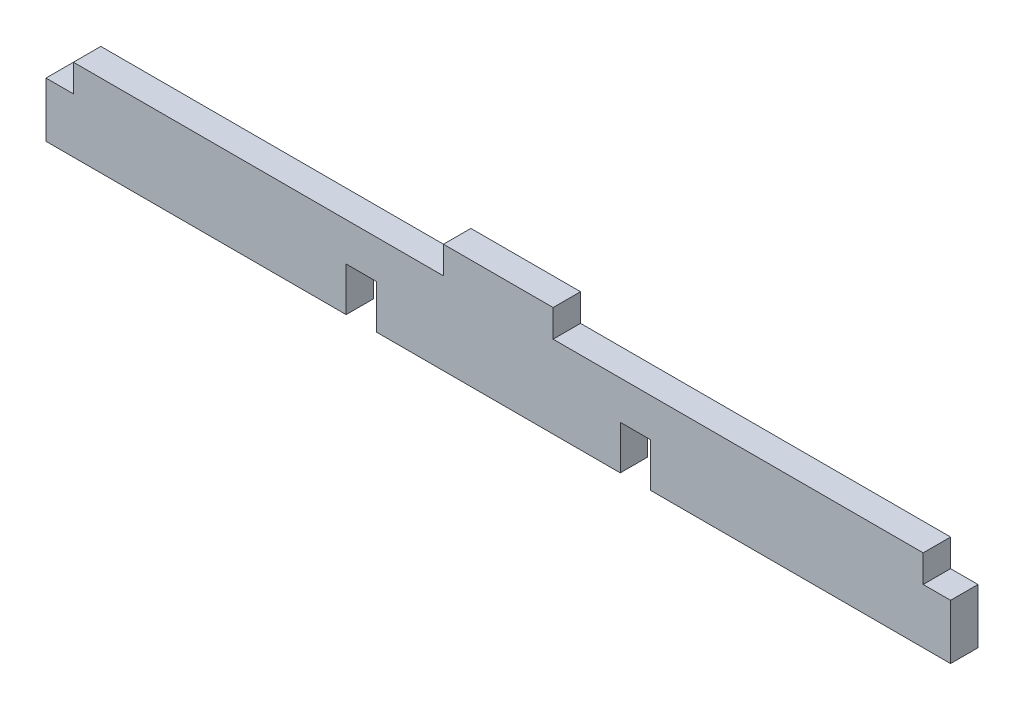
SolidWorks part; units mm, degrees
ref_plane "Front Plane" through (0, 0, 0) normal (0, 0, 1) x (1, 0, 0)
ref_plane "Top Plane" through (0, 0, 0) normal (0, 1, 0) x (1, 0, 0)
ref_plane "Right Plane" through (0, 0, 0) normal (1, 0, 0) x (0, 0, -1)
sketch "Model" plane through (0, 0, 0) normal (0, 0, 1) x (1, 0, 0)
  line L0 (388.2957, -195.6456) -> (388.2957, -203.6456)
  line L1 (393.7957, -195.6456) -> (388.2957, -195.6456)
  line L2 (493.5457, -188.6456) -> (426.0457, -188.6456)
  line L3 (393.7957, -203.6456) -> (393.7957, -195.6456)
  line L4 (393.7957, -203.6456) -> (438.2957, -203.6456)
  line L5 (426.0457, -188.6456) -> (426.0457, -183.6456)
  line L6 (426.0457, -183.6456) -> (406.0457, -183.6456)
  line L7 (493.5457, -193.6456) -> (493.5457, -188.6456)
  line L8 (406.0457, -188.6456) -> (338.5457, -188.6456)
  line L9 (333.5457, -193.6456) -> (333.5457, -203.6456)
  line L10 (443.7957, -195.6456) -> (438.2957, -195.6456)
  line L11 (443.7957, -203.6456) -> (443.7957, -195.6456)
  line L12 (438.2957, -195.6456) -> (438.2957, -203.6456)
  line L13 (338.5457, -188.6456) -> (338.5457, -193.6456)
  line L14 (406.0457, -183.6456) -> (406.0457, -188.6456)
  line L15 (443.7957, -203.6456) -> (498.5457, -203.6456)
  line L16 (498.5457, -203.6456) -> (498.5457, -193.6456)
  line L17 (498.5457, -193.6456) -> (493.5457, -193.6456)
  line L18 (338.5457, -193.6456) -> (333.5457, -193.6456)
  line L19 (333.5457, -203.6456) -> (388.2957, -203.6456)
  line L20 (422.6665, -199.5351) -> (427.6665, -199.5351)
  line L21 (425.6665, -200.5351) -> (427.6665, -199.5351)
  line L22 (425.6665, -198.5351) -> (427.6665, -199.5351)
  line L23 (420.1665, -197.3376) -> (420.1665, -199.5355)
  line L24 (420.1665, -199.5355) -> (419.1487, -199.5355)
  line L25 (419.1487, -199.5355) -> (418.5915, -199.4668)
  line L26 (418.5915, -199.4668) -> (418.2559, -199.3606)
  line L27 (418.2559, -199.3606) -> (418.0826, -199.2264)
  line L28 (418.0826, -199.2264) -> (418.0248, -199.0734)
  line L29 (418.0248, -199.0734) -> (418.0248, -197.8184)
  line L30 (418.0248, -197.8184) -> (418.0455, -197.7197)
  line L31 (418.0455, -197.7197) -> (418.1076, -197.6295)
  line L32 (418.1076, -197.6295) -> (418.3558, -197.475)
  line L33 (418.3558, -197.475) -> (418.7164, -197.372)
  line L34 (418.7164, -197.372) -> (419.1487, -197.3376)
  line L35 (419.1487, -197.3376) -> (420.1665, -197.3376)
  line L36 (420.1665, -201.6456) -> (420.1665, -197.3376)
  line L37 (420.1665, -197.3376) -> (419.1487, -197.3376)
  line L38 (419.1487, -197.3376) -> (418.7164, -197.372)
  line L39 (418.7164, -197.372) -> (418.3558, -197.475)
  line L40 (418.3558, -197.475) -> (418.1076, -197.6295)
  line L41 (418.1076, -197.6295) -> (418.0455, -197.7197)
  line L42 (418.0455, -197.7197) -> (418.0248, -197.8184)
  line L43 (418.0248, -197.8184) -> (418.0248, -199.0733)
  line L44 (418.0248, -199.0733) -> (418.0826, -199.2262)
  line L45 (418.0826, -199.2262) -> (418.2559, -199.3604)
  line L46 (418.2559, -199.3604) -> (418.5915, -199.4666)
  line L47 (418.5915, -199.4666) -> (419.1487, -199.5353)
  line L48 (419.1487, -199.5353) -> (418.5977, -199.5993)
  line L49 (418.5977, -199.5993) -> (418.2559, -199.7039)
  line L50 (418.2559, -199.7039) -> (418.0826, -199.8428)
  line L51 (418.0826, -199.8428) -> (418.0248, -199.9973)
  line L52 (418.0248, -199.9973) -> (418.0248, -201.1648)
  line L53 (418.0248, -201.1648) -> (418.0455, -201.2585)
  line L54 (418.0455, -201.2585) -> (418.1076, -201.3459)
  line L55 (418.1076, -201.3459) -> (418.3558, -201.502)
  line L56 (418.3558, -201.502) -> (418.7195, -201.6097)
  line L57 (418.7195, -201.6097) -> (419.1487, -201.6456)
  line L58 (419.1487, -201.6456) -> (420.1665, -201.6456)
  line L59 (419.1487, -199.5351) -> (420.1665, -199.5351)
  line L60 (420.1665, -199.5351) -> (420.1665, -201.6456)
  line L61 (420.1665, -201.6456) -> (419.1487, -201.6456)
  line L62 (419.1487, -201.6456) -> (418.7195, -201.6097)
  line L63 (418.7195, -201.6097) -> (418.3558, -201.5019)
  line L64 (418.3558, -201.5019) -> (418.1076, -201.3458)
  line L65 (418.1076, -201.3458) -> (418.0455, -201.2584)
  line L66 (418.0455, -201.2584) -> (418.0248, -201.1648)
  line L67 (418.0248, -201.1648) -> (418.0248, -199.9972)
  line L68 (418.0248, -199.9972) -> (418.0826, -199.8426)
  line L69 (418.0826, -199.8426) -> (418.2559, -199.7037)
  line L70 (418.2559, -199.7037) -> (418.5977, -199.5991)
  line L71 (418.5977, -199.5991) -> (419.1487, -199.5351)
  line L72 (417.1696, -197.3376) -> (417.1696, -201.6456)
  line L73 (417.1696, -201.6456) -> (415.0404, -201.6456)
  line L74 (415.0404, -201.6456) -> (417.1696, -201.6456)
  line L75 (417.1696, -201.6456) -> (417.1696, -199.5166)
  line L76 (417.1696, -199.5166) -> (415.3401, -199.5166)
  line L77 (415.3401, -199.5166) -> (417.1696, -199.5166)
  line L78 (417.1696, -199.5166) -> (417.1696, -197.3376)
  line L79 (413.0487, -197.3376) -> (413.4897, -197.3728)
  line L80 (413.4897, -197.3728) -> (413.8511, -197.4781)
  line L81 (413.8511, -197.4781) -> (414.0922, -197.6334)
  line L82 (414.0922, -197.6334) -> (414.1525, -197.7222)
  line L83 (414.1525, -197.7222) -> (414.1726, -197.8184)
  line L84 (414.1726, -197.8184) -> (414.1525, -197.7222)
  line L85 (414.1525, -197.7222) -> (414.0922, -197.6334)
  line L86 (414.0922, -197.6334) -> (413.8511, -197.4781)
  line L87 (413.8511, -197.4781) -> (413.4897, -197.3728)
  line L88 (412.6077, -197.3728) -> (412.2464, -197.4781)
  line L89 (412.2464, -197.4781) -> (412.0052, -197.6334)
  line L90 (412.0052, -197.6334) -> (411.9449, -197.7222)
  line L91 (411.9449, -197.7222) -> (411.9248, -197.8184)
  line L92 (411.9248, -197.8184) -> (411.9248, -199.529)
  line L93 (411.9248, -199.529) -> (411.9449, -199.6252)
  line L94 (411.9449, -199.6252) -> (412.0052, -199.714)
  line L95 (412.0052, -199.714) -> (412.2464, -199.8694)
  line L96 (412.2464, -199.8694) -> (412.6077, -199.9747)
  line L97 (412.6077, -199.9747) -> (413.0487, -200.0098)
  line L98 (413.0487, -200.0098) -> (413.7231, -199.9099)
  line L99 (413.7231, -199.9099) -> (413.9541, -199.7835)
  line L100 (413.9541, -199.7835) -> (414.1726, -199.529)
  line L101 (414.1726, -199.529) -> (414.1726, -201.6456)
  line L102 (414.1726, -201.6456) -> (411.9997, -201.6456)
  line L103 (411.9997, -201.6456) -> (414.1726, -201.6456)
  line L104 (414.1726, -201.6456) -> (414.1726, -199.529)
  line L105 (414.1726, -199.529) -> (413.9541, -199.7835)
  line L106 (413.9541, -199.7835) -> (413.7231, -199.9099)
  line L107 (413.7231, -199.9099) -> (413.0487, -200.0098)
  line L108 (413.0487, -200.0098) -> (412.6077, -199.9747)
  line L109 (412.6077, -199.9747) -> (412.2464, -199.8694)
  line L110 (412.2464, -199.8694) -> (412.0052, -199.714)
  line L111 (412.0052, -199.714) -> (411.9449, -199.6252)
  line L112 (411.9449, -199.6252) -> (411.9248, -199.529)
  line L113 (411.9248, -199.529) -> (411.9248, -197.8184)
  line L114 (411.9248, -197.8184) -> (411.9449, -197.7222)
  line L115 (411.9449, -197.7222) -> (412.0052, -197.6334)
  line L116 (412.0052, -197.6334) -> (412.2464, -197.4781)
  line L117 (412.2464, -197.4781) -> (412.6077, -197.3728)
  line L118 (412.6077, -197.3728) -> (413.0487, -197.3376)
  line L119 (409.4248, -199.5351) -> (404.4248, -199.5351)
  line L120 (406.4248, -198.5351) -> (404.4248, -199.5351)
  line L121 (406.4248, -200.5351) -> (404.4248, -199.5351)
  line L122 (491.5457, -202.8873) -> (489.3478, -202.8873)
  line L123 (489.3478, -202.8873) -> (489.3478, -201.8695)
  line L124 (489.3478, -201.8695) -> (489.4165, -201.3123)
  line L125 (489.4165, -201.3123) -> (489.5227, -200.9766)
  line L126 (489.5227, -200.9766) -> (489.6569, -200.8034)
  line L127 (489.6569, -200.8034) -> (489.8099, -200.7456)
  line L128 (489.8099, -200.7456) -> (491.0649, -200.7456)
  line L129 (491.0649, -200.7456) -> (491.1636, -200.7663)
  line L130 (491.1636, -200.7663) -> (491.2538, -200.8283)
  line L131 (491.2538, -200.8283) -> (491.4083, -201.0765)
  line L132 (491.4083, -201.0765) -> (491.5113, -201.4371)
  line L133 (491.5113, -201.4371) -> (491.5457, -201.8695)
  line L134 (491.5457, -201.8695) -> (491.5457, -202.8873)
  line L135 (487.2377, -202.8873) -> (491.5457, -202.8873)
  line L136 (491.5457, -202.8873) -> (491.5457, -201.8695)
  line L137 (491.5457, -201.8695) -> (491.5113, -201.4371)
  line L138 (491.5113, -201.4371) -> (491.4083, -201.0765)
  line L139 (491.4083, -201.0765) -> (491.2538, -200.8283)
  line L140 (491.2538, -200.8283) -> (491.1636, -200.7663)
  line L141 (491.1636, -200.7663) -> (491.0649, -200.7456)
  line L142 (491.0649, -200.7456) -> (489.81, -200.7456)
  line L143 (489.81, -200.7456) -> (489.6571, -200.8034)
  line L144 (489.6571, -200.8034) -> (489.5228, -200.9766)
  line L145 (489.5228, -200.9766) -> (489.4167, -201.3123)
  line L146 (489.4167, -201.3123) -> (489.348, -201.8695)
  line L147 (489.348, -201.8695) -> (489.284, -201.3185)
  line L148 (489.284, -201.3185) -> (489.1794, -200.9766)
  line L149 (489.1794, -200.9766) -> (489.0405, -200.8034)
  line L150 (489.0405, -200.8034) -> (488.886, -200.7456)
  line L151 (488.886, -200.7456) -> (487.7185, -200.7456)
  line L152 (487.7185, -200.7456) -> (487.6248, -200.7663)
  line L153 (487.6248, -200.7663) -> (487.5374, -200.8283)
  line L154 (487.5374, -200.8283) -> (487.3813, -201.0765)
  line L155 (487.3813, -201.0765) -> (487.2736, -201.4402)
  line L156 (487.2736, -201.4402) -> (487.2377, -201.8695)
  line L157 (487.2377, -201.8695) -> (487.2377, -202.8873)
  line L158 (489.3482, -201.8695) -> (489.3482, -202.8873)
  line L159 (489.3482, -202.8873) -> (487.2377, -202.8873)
  line L160 (487.2377, -202.8873) -> (487.2377, -201.8695)
  line L161 (487.2377, -201.8695) -> (487.2736, -201.4402)
  line L162 (487.2736, -201.4402) -> (487.3814, -201.0765)
  line L163 (487.3814, -201.0765) -> (487.5375, -200.8283)
  line L164 (487.5375, -200.8283) -> (487.6249, -200.7663)
  line L165 (487.6249, -200.7663) -> (487.7185, -200.7456)
  line L166 (487.7185, -200.7456) -> (488.8861, -200.7456)
  line L167 (488.8861, -200.7456) -> (489.0407, -200.8034)
  line L168 (489.0407, -200.8034) -> (489.1796, -200.9766)
  line L169 (489.1796, -200.9766) -> (489.2842, -201.3185)
  line L170 (489.2842, -201.3185) -> (489.3482, -201.8695)
  line L171 (491.0649, -197.6425) -> (491.1611, -197.6626)
  line L172 (491.1611, -197.6626) -> (491.2499, -197.7229)
  line L173 (491.2499, -197.7229) -> (491.4052, -197.9641)
  line L174 (491.4052, -197.9641) -> (491.5105, -198.3254)
  line L175 (491.5105, -198.3254) -> (491.5457, -198.7664)
  line L176 (491.5457, -198.7664) -> (491.5105, -199.2074)
  line L177 (491.5105, -199.2074) -> (491.4052, -199.5688)
  line L178 (491.4052, -199.5688) -> (491.2499, -199.8099)
  line L179 (491.2499, -199.8099) -> (491.1611, -199.8702)
  line L180 (491.1611, -199.8702) -> (491.0649, -199.8903)
  line L181 (491.0649, -199.8903) -> (487.7185, -199.8903)
  line L182 (487.7185, -199.8903) -> (487.6223, -199.8702)
  line L183 (487.6223, -199.8702) -> (487.5335, -199.8099)
  line L184 (487.5335, -199.8099) -> (487.3782, -199.5688)
  line L185 (487.3782, -199.5688) -> (487.2729, -199.2074)
  line L186 (487.2729, -199.2074) -> (487.2377, -198.7664)
  line L187 (487.2377, -198.7664) -> (487.2729, -198.3254)
  line L188 (487.2729, -198.3254) -> (487.3782, -197.9641)
  line L189 (487.3782, -197.9641) -> (487.5335, -197.7229)
  line L190 (487.5335, -197.7229) -> (487.6223, -197.6626)
  line L191 (487.6223, -197.6626) -> (487.7185, -197.6425)
  line L192 (487.7185, -197.6425) -> (488.0244, -197.6425)
  line L193 (488.0244, -197.6425) -> (487.7185, -197.6425)
  line L194 (487.7185, -197.6425) -> (487.6223, -197.6626)
  line L195 (487.6223, -197.6626) -> (487.5335, -197.7229)
  line L196 (487.5335, -197.7229) -> (487.3782, -197.9641)
  line L197 (487.3782, -197.9641) -> (487.2729, -198.3254)
  line L198 (487.2729, -198.3254) -> (487.2377, -198.7664)
  line L199 (487.2377, -198.7664) -> (487.2729, -199.2074)
  line L200 (487.2729, -199.2074) -> (487.3782, -199.5688)
  line L201 (487.3782, -199.5688) -> (487.5335, -199.8099)
  line L202 (487.5335, -199.8099) -> (487.6223, -199.8702)
  line L203 (487.6223, -199.8702) -> (487.7185, -199.8903)
  line L204 (487.7185, -199.8903) -> (491.0649, -199.8903)
  line L205 (491.0649, -199.8903) -> (491.1611, -199.8702)
  line L206 (491.1611, -199.8702) -> (491.2499, -199.8099)
  line L207 (491.2499, -199.8099) -> (491.4052, -199.5688)
  line L208 (491.4052, -199.5688) -> (491.5105, -199.2074)
  line L209 (491.5105, -199.2074) -> (491.5457, -198.7664)
  line L210 (491.5457, -198.7664) -> (491.5105, -198.3254)
  line L211 (491.5105, -198.3254) -> (491.4052, -197.9641)
  line L212 (491.4052, -197.9641) -> (491.2499, -197.7229)
  line L213 (491.2499, -197.7229) -> (491.1611, -197.6626)
  line L214 (489.3917, -197.6425) -> (489.3917, -198.7539)
  line L215 (489.3917, -198.7539) -> (489.3917, -197.6425)
  line L216 (489.3917, -197.6425) -> (491.0649, -197.6425)
  line L217 (491.5457, -195.7695) -> (491.5105, -196.2105)
  line L218 (491.5105, -196.2105) -> (491.4052, -196.5718)
  line L219 (491.4052, -196.5718) -> (491.2499, -196.813)
  line L220 (491.2499, -196.813) -> (491.1611, -196.8733)
  line L221 (491.1611, -196.8733) -> (491.0649, -196.8934)
  line L222 (491.0649, -196.8934) -> (491.1611, -196.8733)
  line L223 (491.1611, -196.8733) -> (491.2499, -196.813)
  line L224 (491.2499, -196.813) -> (491.4052, -196.5718)
  line L225 (491.4052, -196.5718) -> (491.5105, -196.2105)
  line L226 (491.5105, -195.3285) -> (491.4052, -194.9671)
  line L227 (491.4052, -194.9671) -> (491.2499, -194.7259)
  line L228 (491.2499, -194.7259) -> (491.1611, -194.6657)
  line L229 (491.1611, -194.6657) -> (491.0649, -194.6456)
  line L230 (491.0649, -194.6456) -> (489.3543, -194.6456)
  line L231 (489.3543, -194.6456) -> (489.258, -194.6657)
  line L232 (489.258, -194.6657) -> (489.1693, -194.7259)
  line L233 (489.1693, -194.7259) -> (489.0139, -194.9671)
  line L234 (489.0139, -194.9671) -> (488.9086, -195.3285)
  line L235 (488.9086, -195.3285) -> (488.8735, -195.7695)
  line L236 (488.8735, -195.7695) -> (488.9734, -196.4438)
  line L237 (488.9734, -196.4438) -> (489.0998, -196.6748)
  line L238 (489.0998, -196.6748) -> (489.3543, -196.8934)
  line L239 (489.3543, -196.8934) -> (487.2377, -196.8934)
  line L240 (487.2377, -196.8934) -> (487.2377, -194.7205)
  line L241 (487.2377, -194.7205) -> (487.2377, -196.8934)
  line L242 (487.2377, -196.8934) -> (489.3543, -196.8934)
  line L243 (489.3543, -196.8934) -> (489.0998, -196.6748)
  line L244 (489.0998, -196.6748) -> (488.9734, -196.4438)
  line L245 (488.9734, -196.4438) -> (488.8735, -195.7695)
  line L246 (488.8735, -195.7695) -> (488.9086, -195.3285)
  line L247 (488.9086, -195.3285) -> (489.0139, -194.9671)
  line L248 (489.0139, -194.9671) -> (489.1693, -194.7259)
  line L249 (489.1693, -194.7259) -> (489.258, -194.6657)
  line L250 (489.258, -194.6657) -> (489.3543, -194.6456)
  line L251 (489.3543, -194.6456) -> (491.0649, -194.6456)
  line L252 (491.0649, -194.6456) -> (491.1611, -194.6657)
  line L253 (491.1611, -194.6657) -> (491.2499, -194.7259)
  line L254 (491.2499, -194.7259) -> (491.4052, -194.9671)
  line L255 (491.4052, -194.9671) -> (491.5105, -195.3285)
  line L256 (491.5105, -195.3285) -> (491.5457, -195.7695)
  line L257 (486.5457, -191.1456) -> (491.5457, -191.1456)
  line L258 (489.5457, -192.1456) -> (491.5457, -191.1456)
  line L259 (489.5457, -190.1456) -> (491.5457, -191.1456)
  line L260 (345.5457, -200.8903) -> (343.3478, -200.8903)
  line L261 (343.3478, -200.8903) -> (343.3478, -199.8725)
  line L262 (343.3478, -199.8725) -> (343.4165, -199.3153)
  line L263 (343.4165, -199.3153) -> (343.5227, -198.9797)
  line L264 (343.5227, -198.9797) -> (343.6569, -198.8064)
  line L265 (343.6569, -198.8064) -> (343.8099, -198.7486)
  line L266 (343.8099, -198.7486) -> (345.0649, -198.7486)
  line L267 (345.0649, -198.7486) -> (345.1636, -198.7693)
  line L268 (345.1636, -198.7693) -> (345.2538, -198.8314)
  line L269 (345.2538, -198.8314) -> (345.4083, -199.0796)
  line L270 (345.4083, -199.0796) -> (345.5113, -199.4402)
  line L271 (345.5113, -199.4402) -> (345.5457, -199.8725)
  line L272 (345.5457, -199.8725) -> (345.5457, -200.8903)
  line L273 (341.2377, -200.8903) -> (345.5457, -200.8903)
  line L274 (345.5457, -200.8903) -> (345.5457, -199.8725)
  line L275 (345.5457, -199.8725) -> (345.5113, -199.4402)
  line L276 (345.5113, -199.4402) -> (345.4083, -199.0796)
  line L277 (345.4083, -199.0796) -> (345.2538, -198.8314)
  line L278 (345.2538, -198.8314) -> (345.1636, -198.7693)
  line L279 (345.1636, -198.7693) -> (345.0649, -198.7486)
  line L280 (345.0649, -198.7486) -> (343.81, -198.7486)
  line L281 (343.81, -198.7486) -> (343.6571, -198.8064)
  line L282 (343.6571, -198.8064) -> (343.5228, -198.9797)
  line L283 (343.5228, -198.9797) -> (343.4167, -199.3153)
  line L284 (343.4167, -199.3153) -> (343.348, -199.8725)
  line L285 (343.348, -199.8725) -> (343.284, -199.3215)
  line L286 (343.284, -199.3215) -> (343.1794, -198.9797)
  line L287 (343.1794, -198.9797) -> (343.0405, -198.8064)
  line L288 (343.0405, -198.8064) -> (342.886, -198.7486)
  line L289 (342.886, -198.7486) -> (341.7185, -198.7486)
  line L290 (341.7185, -198.7486) -> (341.6248, -198.7693)
  line L291 (341.6248, -198.7693) -> (341.5374, -198.8314)
  line L292 (341.5374, -198.8314) -> (341.3813, -199.0796)
  line L293 (341.3813, -199.0796) -> (341.2736, -199.4433)
  line L294 (341.2736, -199.4433) -> (341.2377, -199.8725)
  line L295 (341.2377, -199.8725) -> (341.2377, -200.8903)
  line L296 (343.3482, -199.8725) -> (343.3482, -200.8903)
  line L297 (343.3482, -200.8903) -> (341.2377, -200.8903)
  line L298 (341.2377, -200.8903) -> (341.2377, -199.8725)
  line L299 (341.2377, -199.8725) -> (341.2736, -199.4433)
  line L300 (341.2736, -199.4433) -> (341.3814, -199.0796)
  line L301 (341.3814, -199.0796) -> (341.5375, -198.8314)
  line L302 (341.5375, -198.8314) -> (341.6249, -198.7693)
  line L303 (341.6249, -198.7693) -> (341.7185, -198.7486)
  line L304 (341.7185, -198.7486) -> (342.8861, -198.7486)
  line L305 (342.8861, -198.7486) -> (343.0407, -198.8064)
  line L306 (343.0407, -198.8064) -> (343.1796, -198.9797)
  line L307 (343.1796, -198.9797) -> (343.2842, -199.3215)
  line L308 (343.2842, -199.3215) -> (343.3482, -199.8725)
  line L309 (341.2316, -197.8934) -> (345.5457, -197.8934)
  line L310 (345.5457, -195.7695) -> (345.5105, -196.2105)
  line L311 (345.5105, -196.2105) -> (345.4052, -196.5718)
  line L312 (345.4052, -196.5718) -> (345.2499, -196.813)
  line L313 (345.2499, -196.813) -> (345.1611, -196.8733)
  line L314 (345.1611, -196.8733) -> (345.0649, -196.8934)
  line L315 (345.0649, -196.8934) -> (345.1611, -196.8733)
  line L316 (345.1611, -196.8733) -> (345.2499, -196.813)
  line L317 (345.2499, -196.813) -> (345.4052, -196.5718)
  line L318 (345.4052, -196.5718) -> (345.5105, -196.2105)
  line L319 (345.5105, -195.3285) -> (345.4052, -194.9671)
  line L320 (345.4052, -194.9671) -> (345.2499, -194.7259)
  line L321 (345.2499, -194.7259) -> (345.1611, -194.6657)
  line L322 (345.1611, -194.6657) -> (345.0649, -194.6456)
  line L323 (345.0649, -194.6456) -> (343.3543, -194.6456)
  line L324 (343.3543, -194.6456) -> (343.258, -194.6657)
  line L325 (343.258, -194.6657) -> (343.1693, -194.7259)
  line L326 (343.1693, -194.7259) -> (343.0139, -194.9671)
  line L327 (343.0139, -194.9671) -> (342.9086, -195.3285)
  line L328 (342.9086, -195.3285) -> (342.8735, -195.7695)
  line L329 (342.8735, -195.7695) -> (342.9734, -196.4438)
  line L330 (342.9734, -196.4438) -> (343.0998, -196.6748)
  line L331 (343.0998, -196.6748) -> (343.3543, -196.8934)
  line L332 (343.3543, -196.8934) -> (341.2377, -196.8934)
  line L333 (341.2377, -196.8934) -> (341.2377, -194.7205)
  line L334 (341.2377, -194.7205) -> (341.2377, -196.8934)
  line L335 (341.2377, -196.8934) -> (343.3543, -196.8934)
  line L336 (343.3543, -196.8934) -> (343.0998, -196.6748)
  line L337 (343.0998, -196.6748) -> (342.9734, -196.4438)
  line L338 (342.9734, -196.4438) -> (342.8735, -195.7695)
  line L339 (342.8735, -195.7695) -> (342.9086, -195.3285)
  line L340 (342.9086, -195.3285) -> (343.0139, -194.9671)
  line L341 (343.0139, -194.9671) -> (343.1693, -194.7259)
  line L342 (343.1693, -194.7259) -> (343.258, -194.6657)
  line L343 (343.258, -194.6657) -> (343.3543, -194.6456)
  line L344 (343.3543, -194.6456) -> (345.0649, -194.6456)
  line L345 (345.0649, -194.6456) -> (345.1611, -194.6657)
  line L346 (345.1611, -194.6657) -> (345.2499, -194.7259)
  line L347 (345.2499, -194.7259) -> (345.4052, -194.9671)
  line L348 (345.4052, -194.9671) -> (345.5105, -195.3285)
  line L349 (345.5105, -195.3285) -> (345.5457, -195.7695)
  line L350 (345.5457, -191.1456) -> (340.5457, -191.1456)
  line L351 (342.5457, -190.1456) -> (340.5457, -191.1456)
  line L352 (342.5457, -192.1456) -> (340.5457, -191.1456)
  line L353 (416.0457, -190.6456) -> (416.0457, -185.6456)
  line L354 (417.0457, -187.6456) -> (416.0457, -185.6456)
  line L355 (415.0457, -187.6456) -> (416.0457, -185.6456)
  line L356 (420.1665, -191.6456) -> (420.1665, -193.8434)
  line L357 (420.1665, -193.8434) -> (419.1487, -193.8434)
  line L358 (419.1487, -193.8434) -> (418.5915, -193.7747)
  line L359 (418.5915, -193.7747) -> (418.2559, -193.6686)
  line L360 (418.2559, -193.6686) -> (418.0826, -193.5343)
  line L361 (418.0826, -193.5343) -> (418.0248, -193.3814)
  line L362 (418.0248, -193.3814) -> (418.0248, -192.1264)
  line L363 (418.0248, -192.1264) -> (418.0455, -192.0276)
  line L364 (418.0455, -192.0276) -> (418.1076, -191.9375)
  line L365 (418.1076, -191.9375) -> (418.3558, -191.7829)
  line L366 (418.3558, -191.7829) -> (418.7164, -191.6799)
  line L367 (418.7164, -191.6799) -> (419.1487, -191.6456)
  line L368 (419.1487, -191.6456) -> (420.1665, -191.6456)
  line L369 (420.1665, -195.9535) -> (420.1665, -191.6456)
  line L370 (420.1665, -191.6456) -> (419.1487, -191.6456)
  line L371 (419.1487, -191.6456) -> (418.7164, -191.6799)
  line L372 (418.7164, -191.6799) -> (418.3558, -191.7829)
  line L373 (418.3558, -191.7829) -> (418.1076, -191.9374)
  line L374 (418.1076, -191.9374) -> (418.0455, -192.0276)
  line L375 (418.0455, -192.0276) -> (418.0248, -192.1263)
  line L376 (418.0248, -192.1263) -> (418.0248, -193.3812)
  line L377 (418.0248, -193.3812) -> (418.0826, -193.5342)
  line L378 (418.0826, -193.5342) -> (418.2559, -193.6684)
  line L379 (418.2559, -193.6684) -> (418.5915, -193.7745)
  line L380 (418.5915, -193.7745) -> (419.1487, -193.8432)
  line L381 (419.1487, -193.8432) -> (418.5977, -193.9072)
  line L382 (418.5977, -193.9072) -> (418.2559, -194.0118)
  line L383 (418.2559, -194.0118) -> (418.0826, -194.1507)
  line L384 (418.0826, -194.1507) -> (418.0248, -194.3052)
  line L385 (418.0248, -194.3052) -> (418.0248, -195.4727)
  line L386 (418.0248, -195.4727) -> (418.0455, -195.5664)
  line L387 (418.0455, -195.5664) -> (418.1076, -195.6538)
  line L388 (418.1076, -195.6538) -> (418.3558, -195.8099)
  line L389 (418.3558, -195.8099) -> (418.7195, -195.9176)
  line L390 (418.7195, -195.9176) -> (419.1487, -195.9535)
  line L391 (419.1487, -195.9535) -> (420.1665, -195.9535)
  line L392 (419.1487, -193.843) -> (420.1665, -193.843)
  line L393 (420.1665, -193.843) -> (420.1665, -195.9535)
  line L394 (420.1665, -195.9535) -> (419.1487, -195.9535)
  line L395 (419.1487, -195.9535) -> (418.7195, -195.9176)
  line L396 (418.7195, -195.9176) -> (418.3558, -195.8099)
  line L397 (418.3558, -195.8099) -> (418.1076, -195.6538)
  line L398 (418.1076, -195.6538) -> (418.0455, -195.5663)
  line L399 (418.0455, -195.5663) -> (418.0248, -195.4727)
  line L400 (418.0248, -195.4727) -> (418.0248, -194.3051)
  line L401 (418.0248, -194.3051) -> (418.0826, -194.1505)
  line L402 (418.0826, -194.1505) -> (418.2559, -194.0116)
  line L403 (418.2559, -194.0116) -> (418.5977, -193.907)
  line L404 (418.5977, -193.907) -> (419.1487, -193.843)
  line L405 (417.1696, -191.6456) -> (417.1696, -195.9535)
  line L406 (417.1696, -195.9535) -> (416.1518, -195.9535)
  line L407 (416.1518, -195.9535) -> (415.7179, -195.9176)
  line L408 (415.7179, -195.9176) -> (415.3526, -195.8099)
  line L409 (415.3526, -195.8099) -> (415.1091, -195.6538)
  line L410 (415.1091, -195.6538) -> (415.0482, -195.5664)
  line L411 (415.0482, -195.5664) -> (415.0279, -195.4727)
  line L412 (415.0279, -195.4727) -> (415.0279, -192.1263)
  line L413 (415.0279, -192.1263) -> (415.0482, -192.0299)
  line L414 (415.0482, -192.0299) -> (415.1091, -191.9406)
  line L415 (415.1091, -191.9406) -> (415.3526, -191.7829)
  line L416 (415.3526, -191.7829) -> (415.7085, -191.6799)
  line L417 (415.7085, -191.6799) -> (416.1518, -191.6456)
  line L418 (416.1518, -191.6456) -> (417.1696, -191.6456)
  line L419 (417.1696, -195.9535) -> (417.1696, -191.6456)
  line L420 (417.1696, -191.6456) -> (416.1518, -191.6456)
  line L421 (416.1518, -191.6456) -> (415.7085, -191.6799)
  line L422 (415.7085, -191.6799) -> (415.3526, -191.7829)
  line L423 (415.3526, -191.7829) -> (415.1091, -191.9406)
  line L424 (415.1091, -191.9406) -> (415.0482, -192.0299)
  line L425 (415.0482, -192.0299) -> (415.0279, -192.1263)
  line L426 (415.0279, -192.1263) -> (415.0279, -195.4727)
  line L427 (415.0279, -195.4727) -> (415.0482, -195.5664)
  line L428 (415.0482, -195.5664) -> (415.1091, -195.6538)
  line L429 (415.1091, -195.6538) -> (415.3526, -195.8099)
  line L430 (415.3526, -195.8099) -> (415.7179, -195.9176)
  line L431 (415.7179, -195.9176) -> (416.1518, -195.9535)
  line L432 (416.1518, -195.9535) -> (417.1696, -195.9535)
  line L433 (413.0487, -191.6456) -> (413.4897, -191.6807)
  line L434 (413.4897, -191.6807) -> (413.8511, -191.786)
  line L435 (413.8511, -191.786) -> (414.0922, -191.9413)
  line L436 (414.0922, -191.9413) -> (414.1525, -192.0301)
  line L437 (414.1525, -192.0301) -> (414.1726, -192.1263)
  line L438 (414.1726, -192.1263) -> (414.1525, -192.0301)
  line L439 (414.1525, -192.0301) -> (414.0922, -191.9413)
  line L440 (414.0922, -191.9413) -> (413.8511, -191.786)
  line L441 (413.8511, -191.786) -> (413.4897, -191.6807)
  line L442 (412.6077, -191.6807) -> (412.2464, -191.786)
  line L443 (412.2464, -191.786) -> (412.0052, -191.9413)
  line L444 (412.0052, -191.9413) -> (411.9449, -192.0301)
  line L445 (411.9449, -192.0301) -> (411.9248, -192.1263)
  line L446 (411.9248, -192.1263) -> (411.9248, -193.837)
  line L447 (411.9248, -193.837) -> (411.9449, -193.9332)
  line L448 (411.9449, -193.9332) -> (412.0052, -194.022)
  line L449 (412.0052, -194.022) -> (412.2464, -194.1773)
  line L450 (412.2464, -194.1773) -> (412.6077, -194.2826)
  line L451 (412.6077, -194.2826) -> (413.0487, -194.3178)
  line L452 (413.0487, -194.3178) -> (413.7231, -194.2178)
  line L453 (413.7231, -194.2178) -> (413.9541, -194.0914)
  line L454 (413.9541, -194.0914) -> (414.1726, -193.837)
  line L455 (414.1726, -193.837) -> (414.1726, -195.9535)
  line L456 (414.1726, -195.9535) -> (411.9997, -195.9535)
  line L457 (411.9997, -195.9535) -> (414.1726, -195.9535)
  line L458 (414.1726, -195.9535) -> (414.1726, -193.837)
  line L459 (414.1726, -193.837) -> (413.9541, -194.0914)
  line L460 (413.9541, -194.0914) -> (413.7231, -194.2178)
  line L461 (413.7231, -194.2178) -> (413.0487, -194.3178)
  line L462 (413.0487, -194.3178) -> (412.6077, -194.2826)
  line L463 (412.6077, -194.2826) -> (412.2464, -194.1773)
  line L464 (412.2464, -194.1773) -> (412.0052, -194.022)
  line L465 (412.0052, -194.022) -> (411.9449, -193.9332)
  line L466 (411.9449, -193.9332) -> (411.9248, -193.837)
  line L467 (411.9248, -193.837) -> (411.9248, -192.1263)
  line L468 (411.9248, -192.1263) -> (411.9449, -192.0301)
  line L469 (411.9449, -192.0301) -> (412.0052, -191.9413)
  line L470 (412.0052, -191.9413) -> (412.2464, -191.786)
  line L471 (412.2464, -191.786) -> (412.6077, -191.6807)
  line L472 (412.6077, -191.6807) -> (413.0487, -191.6456)
  line L473 (363.2471, -192.9265) -> (363.9698, -192.7158)
  line L474 (367.0996, -197.0284) -> (367.0996, -201.2614)
  line L475 (362.7539, -201.2614) -> (367.0996, -201.2614)
  line L476 (362.604, -197.0284) -> (362.604, -193.6071)
  line L477 (362.6442, -193.4147) -> (362.7648, -193.2371)
  line L478 (367.0996, -197.0284) -> (366.6626, -197.5373)
  line L479 (366.4565, -192.9265) -> (366.9389, -193.2371)
  line L480 (365.7338, -192.7158) -> (366.4565, -192.9265)
  line L481 (363.2471, -197.709) -> (362.7648, -197.3984)
  line L482 (362.604, -193.6071) -> (362.6442, -193.4147)
  line L483 (364.8518, -197.99) -> (363.9698, -197.9197)
  line L484 (366.2005, -197.7901) -> (364.8518, -197.99)
  line L485 (362.6442, -197.2208) -> (362.604, -197.0284)
  line L486 (362.7648, -193.2371) -> (363.2471, -192.9265)
  line L487 (379.0874, -197.0412) -> (379.0874, -192.6456)
  line L488 (363.9698, -197.9197) -> (363.2471, -197.709)
  line L489 (366.6626, -197.5373) -> (366.2005, -197.7901)
  line L490 (362.7648, -197.3984) -> (362.6442, -197.2208)
  line L491 (374.8455, -200.4871) -> (374.8041, -200.2999)
  line L492 (375.466, -200.9743) -> (374.9696, -200.6619)
  line L493 (373.0935, -192.6456) -> (373.0935, -197.0784)
  line L494 (374.8041, -200.2999) -> (374.8041, -197.9649)
  line L495 (375.2662, -197.378) -> (375.9499, -197.1688)
  line L496 (363.9698, -192.7158) -> (364.8518, -192.6456)
  line L497 (374.9196, -197.6558) -> (375.2662, -197.378)
  line L498 (375.9374, -196.9039) -> (377.0519, -197.0412)
  line L499 (376.1934, -201.1896) -> (377.0519, -201.2614)
  line L500 (367.0594, -193.4147) -> (366.9389, -193.2371)
  line L501 (374.8041, -193.6072) -> (374.8041, -196.1172)
  line L502 (367.0594, -193.4147) -> (367.0996, -193.6071)
  line L503 (374.8455, -200.4871) -> (374.9696, -200.6619)
  line L504 (373.0935, -201.2614) -> (368.8351, -201.2614)
  line L505 (375.9499, -197.1688) -> (377.0519, -197.0412)
  line L506 (373.0935, -192.6456) -> (368.8351, -192.6456)
  line L507 (373.0935, -197.0784) -> (369.4346, -197.0784)
  line L508 (374.8041, -197.9649) -> (374.9196, -197.6558)
  line L509 (376.1871, -192.7143) -> (375.466, -192.9203)
  line L510 (373.0935, -197.0784) -> (373.0935, -201.2614)
  line L511 (379.0874, -192.6456) -> (377.0519, -192.6456)
  line L512 (374.8041, -196.1172) -> (374.9196, -196.4231)
  line L513 (374.9696, -193.2294) -> (374.8455, -193.4097)
  line L514 (377.0519, -192.6456) -> (376.1871, -192.7143)
  line L515 (374.8455, -193.4097) -> (374.8041, -193.6072)
  line L516 (374.9196, -196.4231) -> (375.2662, -196.6916)
  line L517 (379.0874, -201.2614) -> (379.0874, -197.0412)
  line L518 (375.466, -192.9203) -> (374.9696, -193.2294)
  line L519 (377.0519, -197.0412) -> (379.0874, -197.0412)
  line L520 (377.0519, -201.2614) -> (379.0874, -201.2614)
  line L521 (376.1934, -201.1896) -> (375.466, -200.9743)
  line L522 (375.2662, -196.6916) -> (375.9374, -196.9039)
  line L523 (364.8518, -192.6456) -> (365.7338, -192.7158)
  line L524 (379.0874, -191.6456) -> (362.7539, -191.6456)
sketch "Sketch2" plane through (0, 0, 0) normal (0, 0, 1) x (1, 0, 0)
  line L0 (443.7957, -203.6456) -> (498.5457, -203.6456) construction
  line L1 (443.7957, -203.6456) -> (443.7957, -195.6456) construction
  line L2 (443.7957, -195.6456) -> (438.2957, -195.6456) construction
  line L3 (438.2957, -195.6456) -> (438.2957, -203.6456) construction
  line L4 (393.7957, -203.6456) -> (438.2957, -203.6456) construction
  line L5 (393.7957, -203.6456) -> (393.7957, -195.6456) construction
  line L6 (393.7957, -195.6456) -> (388.2957, -195.6456) construction
  line L7 (388.2957, -195.6456) -> (388.2957, -203.6456) construction
  line L8 (333.5457, -203.6456) -> (388.2957, -203.6456) construction
  line L9 (333.5457, -193.6456) -> (333.5457, -203.6456) construction
  line L10 (338.5457, -193.6456) -> (333.5457, -193.6456) construction
  line L11 (338.5457, -188.6456) -> (338.5457, -193.6456) construction
  line L12 (406.0457, -188.6456) -> (338.5457, -188.6456) construction
  line L13 (406.0457, -183.6456) -> (406.0457, -188.6456) construction
  line L14 (426.0457, -183.6456) -> (406.0457, -183.6456) construction
  line L15 (426.0457, -188.6456) -> (426.0457, -183.6456) construction
  line L16 (493.5457, -188.6456) -> (426.0457, -188.6456) construction
  line L17 (493.5457, -193.6456) -> (493.5457, -188.6456) construction
  line L18 (498.5457, -193.6456) -> (493.5457, -193.6456) construction
  line L19 (498.5457, -203.6456) -> (498.5457, -193.6456) construction
  line L20 (443.7957, -203.6456) -> (443.7957, -195.6456)
  line L21 (443.7957, -195.6456) -> (438.2957, -195.6456)
  line L22 (438.2957, -195.6456) -> (438.2957, -203.6456)
  line L23 (393.7957, -203.6456) -> (438.2957, -203.6456)
  line L24 (393.7957, -203.6456) -> (393.7957, -195.6456)
  line L25 (393.7957, -195.6456) -> (388.2957, -195.6456)
  line L26 (388.2957, -195.6456) -> (388.2957, -203.6456)
  line L27 (333.5457, -203.6456) -> (388.2957, -203.6456)
  line L28 (333.5457, -193.6456) -> (333.5457, -203.6456)
  line L29 (338.5457, -193.6456) -> (333.5457, -193.6456)
  line L30 (338.5457, -188.6456) -> (338.5457, -193.6456)
  line L31 (406.0457, -188.6456) -> (338.5457, -188.6456)
  line L32 (406.0457, -183.6456) -> (406.0457, -188.6456)
  line L33 (426.0457, -183.6456) -> (406.0457, -183.6456)
  line L34 (426.0457, -188.6456) -> (426.0457, -183.6456)
  line L35 (493.5457, -188.6456) -> (426.0457, -188.6456)
  line L36 (493.5457, -193.6456) -> (493.5457, -188.6456)
  line L37 (498.5457, -193.6456) -> (493.5457, -193.6456)
  line L38 (498.5457, -203.6456) -> (498.5457, -193.6456)
  line L39 (443.7957, -203.6456) -> (498.5457, -203.6456)
extrude "Boss-Extrude1" add sketch "Sketch2" along normal mid plane 5
ref_plane "Plane1" through (416.0457, 0, 0) normal (1, 0, 0) x (0, 0, -1)
